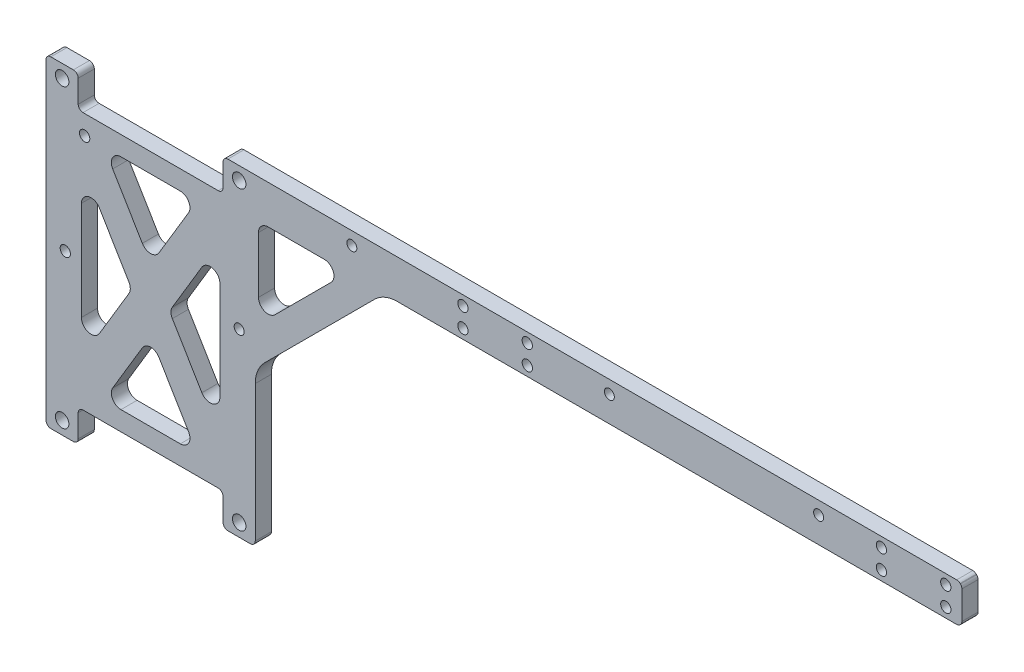
SolidWorks part; units mm, degrees
material "Thornel Mat VMA"
ref_plane "前视基准面" through (0, 0, 0) normal (0, 0, 1) x (1, 0, 0)
ref_plane "上视基准面" through (0, 0, 0) normal (0, 1, 0) x (1, 0, 0)
ref_plane "右视基准面" through (0, 0, 0) normal (1, 0, 0) x (0, 0, -1)
sketch "草图1" plane through (0, 0, 0) normal (0, 0, 1) x (1, 0, 0)
  line L0 (-80, 0) -> (80, 0) construction
  line L1 (-80, 6) -> (80, 6)
  line L2 (-80, 6) -> (-80, -6)
  line L3 (-80, -6) -> (80, -6)
  line L4 (80, 6) -> (80, -6)
  line L5 (-80, 6) -> (80, -6) construction
  line L6 (-80, -6) -> (80, 6) construction
  line L8 (0, -6) -> (0, 6) construction
  circle A0 centre (55, -3) radius 1.6
  circle A1 centre (75, -3) radius 1.6
  circle A2 centre (-75, -3) radius 1.6
  circle A3 centre (-55, -3) radius 1.6
  circle A4 centre (-75, 3) radius 1.6
  circle A5 centre (-55, 3) radius 1.6
  circle A6 centre (55, 3) radius 1.6
  circle A7 centre (75, 3) radius 1.6
  point P0 (0, 0)
  dimension "D6" = 3.2
  dimension "D1" = 160
  dimension "D2" = 12
  dimension "D3" = 20
  dimension "D4" = 5
  dimension "D5" = 5
  dimension "D7" = 3
  dimension "D8" = 20
  dimension "D9" = 3
  dimension "D10" = 3
  dimension "D11" = 3
extrude "凸台-拉伸1" add sketch "草图1" along normal blind 5
chamfer "倒角1" distance 1 angle 45 2 edges at (80, -6, 2.5) (80, 6, 2.5)
sketch "草图2" plane through (0, 0, 0) normal (0, 0, -1) x (-1, 0, 0)
  line L0 (80, 6) -> (80, -6) construction
  line L1 (80, 6) -> (204.5, 6)
  line L2 (80, 6) -> (80, -6)
  line L3 (80, -6) -> (204.5, -6)
  line L4 (204.5, 6) -> (204.5, -6)
  line L5 (-79, 6) -> (80, 6) construction
  line L6 (139.5, -6) -> (139.5, -94)
  line L7 (139.5, -94) -> (204.5, -94)
  line L8 (204.5, -94) -> (204.5, -6)
  line M10 (80, -6) -> (80, 6)
  dimension "D1" = 12
  dimension "D2" = 124.5
  dimension "D3" = 88
  dimension "D4" = 65
  dimension "D5" = 65
extrude "凸台-拉伸2" add sketch "草图2" against normal up to surface (5 mm away) separate body contours L4 L1 L3 M10 | L7 L8 L3 L6 up to face at (53.4, 3, 5)
combine bodies "组合1" operation type add bodies to combine 107 106
chamfer "倒角2" distance 40 angle 45 1 edges at (-139.5, -6, 2.5)
sketch "草图3" plane through (0, 0, 0) normal (0, 0, -1) x (-1, 0, 0)
  line L0 (-79, 6) -> (204.5, 6) construction
  line L1 (144.5, 2) -> (199.5, 2) construction
  line L2 (144.5, 2) -> (144.5, -90) construction
  line L3 (144.5, -90) -> (199.5, -90) construction
  line L4 (199.5, 2) -> (199.5, -90) construction
  line L5 (144.5, 2) -> (199.5, -90) construction
  line L6 (144.5, -90) -> (199.5, 2) construction
  line L7 (172, -44) -> (172, -94) construction
  line L8 (139.5, -94) -> (204.5, -94) construction
  line L10 (149.5, -84) -> (194.5, -84)
  line L11 (149.5, -84) -> (149.5, -104)
  line L12 (149.5, -104) -> (194.5, -104)
  line L13 (194.5, -84) -> (194.5, -104)
  line L14 (149.5, -84) -> (194.5, -104) construction
  line L15 (149.5, -104) -> (194.5, -84) construction
  line L16 (149.5, 16) -> (194.5, 16)
  line L17 (149.5, 16) -> (149.5, -4)
  line L18 (149.5, -4) -> (194.5, -4)
  line L19 (194.5, 16) -> (194.5, -4)
  line L20 (149.5, 16) -> (194.5, -4) construction
  line L21 (149.5, -4) -> (194.5, 16) construction
  circle A0 centre (144.5, -90) radius 2.1
  circle A1 centre (199.5, -90) radius 2.1
  circle A2 centre (144.5, 2) radius 2.1
  circle A3 centre (199.5, 2) radius 2.1
  point P0 (172, -44)
  point P19 (172, 6)
  dimension "D4" = 4.2
  dimension "D1" = 50
  dimension "D2" = 92
  dimension "D3" = 55
  dimension "D5" = 10
  dimension "D6" = 45
  dimension "D7" = 10
  dimension "D8" = 45
extrude "切除-拉伸1" cut sketch "草图3" against normal through all
sketch "草图4" plane through (0, 0, 5) normal (0, 0, 1) x (1, 0, 0)
  line L0 (-195.2084, -92.5656) -> (-140.2084, -0.5656)
  line L1 (-199.5, 2) -> (-144.5, 2)
  line L2 (-199.5, 2) -> (-199.5, -90)
  line L3 (-199.5, -90) -> (-144.5, -90)
  line L4 (-144.5, 2) -> (-144.5, -90)
  line L5 (-199.5, 2) -> (-144.5, -90) construction
  line L6 (-199.5, -90) -> (-144.5, 2) construction
  line L7 (-203.7916, -0.5656) -> (-148.7916, -92.5656)
  line L8 (-203.7916, -87.4344) -> (-148.7916, 4.5656)
  line L9 (-195.2084, 4.5656) -> (-140.2084, -87.4344)
  line L10 (-194.5, -84) -> (-149.5, -84) construction
  line L11 (-194.5, -84) -> (-149.5, -84)
  line L12 (-149.5, -4) -> (-194.5, -4) construction
  line L13 (-149.5, -4) -> (-194.5, -4)
  line L14 (-149.5, 2) -> (-194.5, 2)
  line L15 (-194.5, -90) -> (-149.5, -90)
  line L16 (-149.5, -10) -> (-194.5, -10)
  line L17 (-194.5, -78) -> (-149.5, -78)
  line L18 (-150.5, 2) -> (-150.5, -90)
  line L19 (-205.5, 2) -> (-205.5, -90)
  line L20 (-138.5, 2) -> (-138.5, -90)
  line L21 (-193.5, 2) -> (-193.5, -90)
  point P0 (-172, -44)
  dimension "D1" = 5
  dimension "D2" = 5
  dimension "D3" = 6
  dimension "D4" = 6
  dimension "D5" = 6
  dimension "D6" = 6
extrude "切除-拉伸2" cut sketch "草图4" against normal through all contours L18 L0 L9 | L8 L16 L9 | L0 L17 L7 | L7 L21 L8
sketch "草图5" plane through (0, 0, 0) normal (0, 0, -1) x (-1, 0, 0)
  line L0 (110.8137, -6) -> (138.5, -33.6863)
  line L1 (138.5, -33.6863) -> (138.5, -6)
  line L2 (138.5, -6) -> (110.8137, -6)
  line L5 (99.5, -6) -> (139.5, -46) construction
  line L6 (-79, 6) -> (149.5, 6) construction
  line L8 (150.5, -17.7806) -> (150.5, -70.2194) construction
  dimension "D1" = 8
  dimension "D2" = 12
  dimension "D3" = 12
extrude "切除-拉伸3" cut sketch "草图5" against normal through all
fillet "圆角1" radius 3 15 edges at (-186.5007, -78, 2.5) (-172, -53.7443, 2.5) (-193.5, -70.2194, 2.5) (-193.5, -17.7806, 2.5) (-177.8254, -44, 2.5) (-166.1746, -44, 2.5) (-150.5, -17.7806, 2.5) (-150.5, -70.2194, 2.5) (-172, -34.2557, 2.5) (-186.5007, -10, 2.5) (-157.4993, -10, 2.5) (-110.8137, -6, 2.5) (-138.5, -33.6863, 2.5) (-138.5, -6, 2.5) (-157.4993, -78, 2.5)
fillet "圆角2" radius 1.5 15 edges at (-194.5, -84, 2.5) (-149.5, -84, 2.5) (-139.5, -94, 2.5) (79, -6, 2.5) (80, -5, 2.5) (80, 5, 2.5) (79, 6, 2.5) (-149.5, 6, 2.5) (-149.5, -4, 2.5) (-194.5, -4, 2.5) (-194.5, 6, 2.5) (-204.5, 6, 2.5) (-204.5, -94, 2.5) (-194.5, -94, 2.5) (-149.5, -94, 2.5)
sketch "草图6" plane through (0, 0, 0) normal (0, 0, -1) x (-1, 0, 0)
  line L0 (109.5, 2) -> (144.5, 2) construction
  line L1 (144.5, -38) -> (144.5, 2) construction
  line L2 (109.5, 2) -> (29.5, 2) construction
  line L3 (29.5, 2) -> (-35.5, 2) construction
  circle A0 centre (109.5, 2) radius 1.55
  circle A1 centre (144.5, -38) radius 1.55
  circle A2 centre (29.5, 2) radius 1.55
  circle A3 centre (-35.5, 2) radius 1.55
  dimension "D2" = 3.1
  dimension "D1" = 35
  dimension "D3" = 40
  dimension "D4" = 80
  dimension "D5" = 65
extrude "切除-拉伸4" cut sketch "草图6" against normal through all
fillet "圆角3" radius 10 2 edges at (-99.5, -6, 2.5) (-139.5, -46, 2.5)
sketch "草图7" plane through (0, 0, 5) normal (0, 0, 1) x (1, 0, 0)
  line L0 (-204.5, 4.5) -> (-204.5, -92.5) construction
  line L1 (-196, 6) -> (-203, 6) construction
  circle A0 centre (-192.5, -10) radius 1.6
  circle A1 centre (-198.5, -44) radius 1.6
  dimension "D1" = 3.2
  dimension "D2" = 12
  dimension "D3" = 16
  dimension "D4" = 6
  dimension "D5" = 50
extrude "切除-拉伸5" cut sketch "草图7" against normal through all
